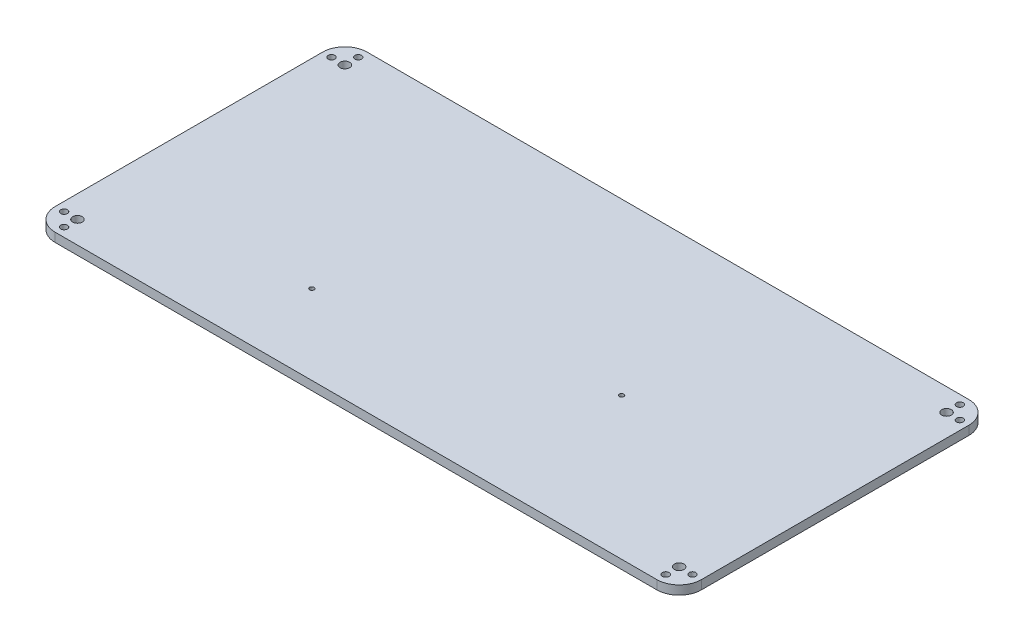
SolidWorks part; units mm, degrees
ref_plane "Front Plane" through (0, 0, 0) normal (0, 0, 1) x (1, 0, 0)
ref_plane "Top Plane" through (0, 0, 0) normal (0, 1, 0) x (1, 0, 0)
ref_plane "Right Plane" through (0, 0, 0) normal (1, 0, 0) x (0, 0, -1)
sketch "Sketch1" plane through (0, 0, 0) normal (0, 1, 0) x (1, 0, 0)
  line L0 (0, 0) -> (145, 0) construction
  line L1 (145, 0) -> (145, -60)
  line L2 (135, -70) -> (0, -70)
  line L3 (0, -70) -> (0, 0)
  line L4 (0, 0) -> (145, 0)
  line L5 (135, -60) -> (141, -60) construction
  line L6 (135, -60) -> (135.5355, -60.5355) construction
  line L7 (135.5355, -60.5355) -> (134.9722, -59.9722) construction
  arc A0 (135, -70) -> (145, -60) centre (135, -60) ccw
  circle A1 centre (135, -60) radius 2.15
  circle A2 centre (141, -60) radius 1.5
  circle A3 centre (135, -66) radius 1.5
  point P7 (145, -70)
  dimension "D4" = 10
  dimension "D5" = 4.3
  dimension "D7" = 3
  dimension "D1" = 145
  dimension "D2" = 70
  dimension "D3" = 145
  dimension "D6" = 6
extrude "Boss-Extrude1" add sketch "Sketch1" along normal blind 4 contours L2 A0 L1 L4 L3 A1
mirror "Mirror1" about plane through (0, 0, 0) normal (1, 0, 0) of "Boss-Extrude1"
mirror "Mirror2" about plane through (0, 0, 0) normal (0, 0, 1) of "Mirror1", "Boss-Extrude1"
sketch "Sketch2" plane through (0, 6, 0) normal (0, 1, 0) x (1, 0, 0)
  circle A0 centre (55.5, -6.3091) radius 1
  circle A1 centre (-55.5, -34.3091) radius 1
extrude "Cut-Extrude1" cut sketch "Sketch2" against normal blind 10
